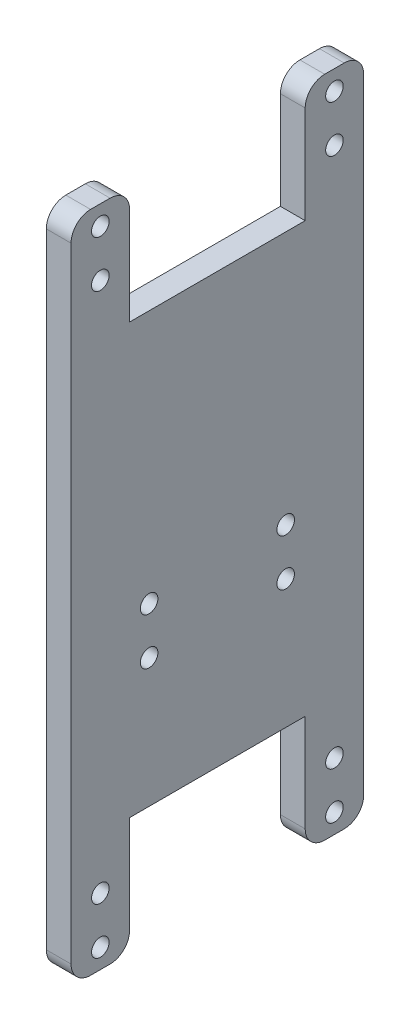
SolidWorks part; units mm, degrees
ref_plane "Alzado" through (0, 0, 0) normal (0, 0, 1) x (1, 0, 0)
ref_plane "Planta" through (0, 0, 0) normal (0, 1, 0) x (1, 0, 0)
ref_plane "Vista lateral" through (0, 0, 0) normal (1, 0, 0) x (0, 0, -1)
sketch "Croquis1" plane through (0, 0, 0) normal (1, 0, 0) x (0, 0, -1)
  line L2 (-22.5, 85) -> (-22.5, 55)
  line L3 (-22.5, 55) -> (22.5, 55)
  line L4 (22.5, 55) -> (22.5, 85)
  line L5 (22.5, 85) -> (37.5, 85)
  line L6 (37.5, 85) -> (37.5, 35)
  line L8 (-37.5, -85) -> (-22.5, -85)
  line L9 (-22.5, -85) -> (-22.5, -55)
  line L10 (-22.5, -55) -> (22.5, -55)
  line L11 (22.5, -55) -> (22.5, -85)
  line L12 (22.5, -85) -> (37.5, -85)
  line L15 (37.5, 35) -> (37.5, -35)
  line L16 (-37.5, 35) -> (-37.5, -35)
  line L21 (-37.5, 85) -> (-37.5, 35)
  line L22 (-37.5, 85) -> (-22.5, 85)
  line L23 (-37.5, -35) -> (-37.5, -85)
  line L26 (37.5, -35) -> (37.5, -85)
  point P1 (37.5, 0)
  point P32 (0, 55)
  dimension "D1" = 15
  dimension "D2" = 70
  dimension "D3" = 30
  dimension "D6" = 50
  dimension "D7" = 45
  dimension "D8" = 30
extrude "Saliente-Extruir1" add sketch "Croquis1" along normal blind 6.35
hole_wizard "Taladro de margen para M41" positions "Croquis2" profile "Croquis3" hole size "M4" standard "Ansi Metric" end condition up to next
sketch "Croquis2" plane through (0, 0, 0) normal (-1, 0, 0) x (0, 0, 1)
  line L0 (0, 55) -> (0, 85) construction
  line L1 (-22.5, 55) -> (22.5, 55) construction
  line L3 (22.5, 85) -> (37.5, 85) construction
  line L4 (0, -55) -> (0, -85) construction
  line L5 (22.5, -55) -> (-22.5, -55) construction
  line L7 (22.5, -85) -> (22.5, -55) construction
  line L8 (37.5, -85) -> (22.5, -85) construction
  line L9 (-30, 80) -> (-22.5, 80) construction
  line L10 (-22.5, 85) -> (-22.5, 55) construction
  line L12 (-30, 80) -> (-30, 85) construction
  line L13 (-37.5, 85) -> (-22.5, 85) construction
  line L15 (22.5, -80) -> (30, -80) construction
  line L16 (30, -80) -> (30, -85) construction
  line L19 (30, -80) -> (30, -68) construction
  line L21 (-30, 68) -> (-30, 80) construction
  line L22 (22.5, 85) -> (37.5, 85) construction
  line L23 (22.5, 55) -> (22.5, 85) construction
  point P0 (30, 68)
  point P3 (30, 80)
  point P15 (-30, 68)
  point P16 (-30, 80)
  point P55 (30, -80)
  point P60 (30, -68)
  point P74 (-30, -80)
  point P75 (-30, -68)
  dimension "D1" = 12
  dimension "D2" = 5
  dimension "D3" = 7.5
sketch "Croquis3" plane through (0, 68, 30) normal (0, 1, 0) x (0, 0, 1)
  line L0 (0, 0) -> (0, 6.35)
  line L1 (0, 6.35) -> (2.25, 6.35)
  line L2 (2.25, 6.35) -> (2.25, 0)
  line L5 (2.25, 0) -> (0, 0)
  line L11 (0, -6.35) -> (0, 107.95) construction
  dimension "Diámetro de taladro hasta el siguiente" = 4.5
  dimension "Profundidad de taladro hasta el siguiente" = 6.35
fillet "Redondeo1" radius 5 8 edges at (3.175, -85, -37.5) (3.175, -85, 37.5) (3.175, 85, -37.5) (3.175, 85, 37.5) (3.175, -85, -22.5) (3.175, -85, 22.5) (3.175, 85, -22.5) (3.175, 85, 22.5)
hole_wizard "Taladro de margen para M42" positions "Croquis4" profile "Croquis5" hole size "M4" standard "Ansi Metric" end condition up to next
sketch "Croquis4" plane through (6.35, 0, 0) normal (1, 0, 0) x (0, 0, -1)
  line L1 (-17.5, -22) -> (-17.5, -10) construction
  line L2 (-17.5, -10) -> (17.5, -10) construction
  line L3 (17.5, -10) -> (17.5, -22) construction
  line L4 (32.5, 85) -> (27.5, 85) construction
  point P0 (-17.5, -10)
  point P2 (17.5, -10)
  point P4 (17.5, -22)
  point P6 (-17.5, -22)
  point P17 (0, -10)
  dimension "D1" = 35
  dimension "D2" = 95
  dimension "D3" = 12
sketch "Croquis5" plane through (6.35, -10, 17.5) normal (0, 1, 0) x (0, 0, -1)
  line L0 (0, 0) -> (0, 6.35)
  line L1 (0, 6.35) -> (2.25, 6.35)
  line L2 (2.25, 6.35) -> (2.25, 0)
  line L5 (2.25, 0) -> (0, 0)
  line L11 (0, -6.35) -> (0, 107.95) construction
  dimension "Diámetro de taladro hasta el siguiente" = 4.5
  dimension "Profundidad de taladro hasta el siguiente" = 6.35
